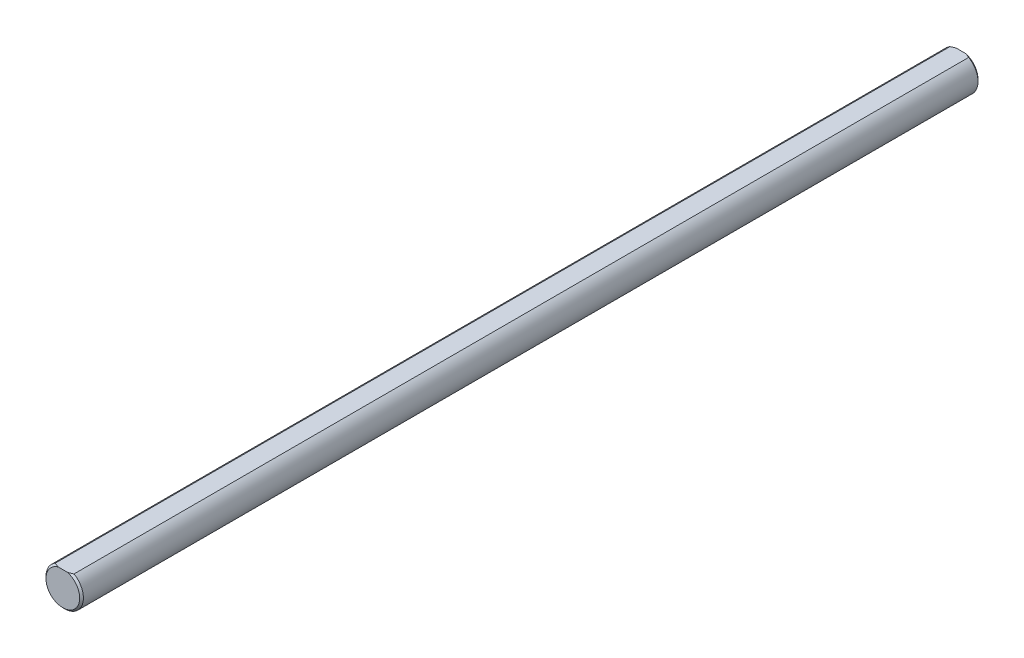
SolidWorks part; units mm, degrees
ref_plane "Front Plane" through (0, 0, 0) normal (0, 0, 1) x (1, 0, 0)
ref_plane "Top Plane" through (0, 0, 0) normal (0, 1, 0) x (1, 0, 0)
ref_plane "Right Plane" through (0, 0, 0) normal (1, 0, 0) x (0, 0, -1)
sketch "Sketch1" plane through (0, 0, 0) normal (0, 0, 1) x (1, 0, 0)
  line L0 (-1.5875, 2.7496) -> (1.5875, 2.7496) construction
  circle A1 centre (0, 0) radius 3.175 construction
  dimension "Diameter" = 6.35
  dimension "Flat Width" = 3.175
sketch "Sketch2" plane through (0, 0, 0) normal (1, 0, 0) x (0, 0, -1)
  line L0 (-76.2, 3.175) -> (76.2, 3.175) construction
  line L1 (0, 3.175) -> (0, -3.175) construction
  line L2 (0, 3.175) -> (0, -3.175) construction
  line L3 (-76.2, 3.175) -> (-76.2, -3.175) construction
  line L4 (-76.2, -3.175) -> (76.2, -3.175) construction
  point P2 (0, 3.175)
  point P3 (63.5, 3.175)
  point P4 (-63.5, 3.175)
  dimension "Length" = 152.4
  dimension "D2" = 12.7
  dimension "D1" = 12.7
  dimension "D-Profile Length" = 152.4
sketch "Sketch3" plane through (0, 0, 0) normal (0, 0, 1) x (1, 0, 0)
  circle A1 centre (0, 0) radius 3.175 construction
  circle A3 centre (0, 0) radius 3.175
extrude "Boss-Extrude2" add sketch "Sketch3" along normal up to vertex (76.2 mm away) and the other way up to vertex (76.2 mm away) up to point (0, 3.175, 76.2) other way up to point (0, 3.175, -76.2)
sketch "Sketch10" plane through (0, 0, 0) normal (0, 0, 1) x (1, 0, 0)
  line L0 (-1.5875, 2.7496) -> (1.5875, 2.7496)
  line L1 (0, 0) -> (0, 3.175) construction
  circle A0 centre (0, 0) radius 3.175 construction
  circle A1 centre (0, 0) radius 3.175 construction
  arc A2 (-1.5875, 2.7496) -> (1.5875, 2.7496) centre (0, 0) cw
extrude "Cut-Extrude5" cut sketch "Sketch10" against normal through all both and the other way through all
chamfer "Chamfer1" distance 0.3175 angle 45 4 edges at (0, -3.175, 76.2) (0, -3.175, -76.2) (0, 2.7496, -76.2) (0, 2.7496, 76.2)
equation "\"D1@Chamfer1\"= \"Diameter@Sketch1\" / 20"
equation "\"D1@Sketch2\"=\"Diameter@Sketch1\"*2"
equation "\"D2@Sketch2\"=\"D1@Sketch2\""
